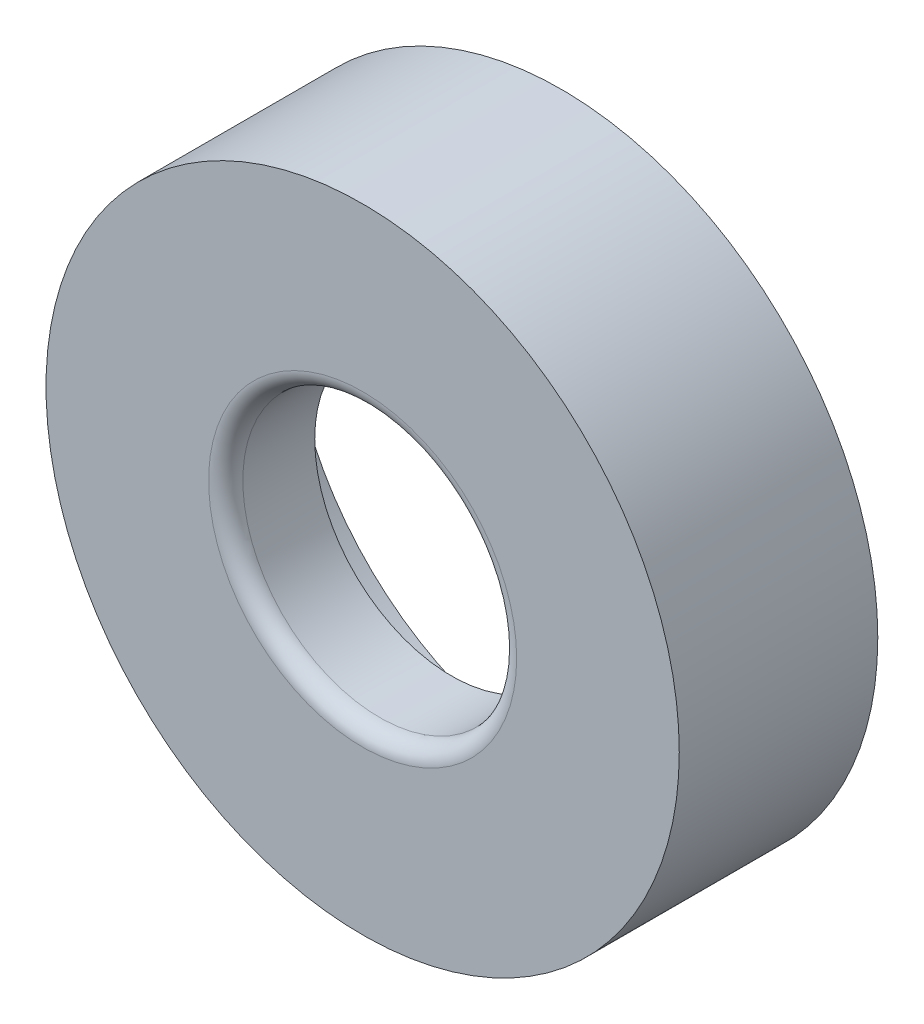
SolidWorks part; units mm, degrees
other "Markup1"
sketch "Sketch4" plane through (94.4065, -10.964, 0) normal (0.175, -0.6068, -0.7753) x (-0.9753, 0.0008, -0.2208)
ref_plane "Front Plane" through (0, 0, 0) normal (0, 0, 1) x (1, 0, 0)
ref_plane "Top Plane" through (0, 0, 0) normal (0, 1, 0) x (1, 0, 0)
ref_plane "Right Plane" through (0, 0, 0) normal (1, 0, 0) x (0, 0, -1)
sketch "Sketch1" plane through (0, 0, 0) normal (0, 0, 1) x (1, 0, 0)
  circle A0 centre (85.2065, -1.764) radius 9.25
  dimension "D1" = 18.5
extrude "Boss-Extrude1" add sketch "Sketch1" along normal blind 5.8
sketch "Sketch2" plane through (0, 0, 5.8) normal (0, 0, 1) x (1, 0, 0)
  circle A0 centre (85.2065, -1.764) radius 4
  dimension "D1" = 8
extrude "Cut-Extrude1" cut sketch "Sketch2" against normal through all
sketch "Sketch3" plane through (0, 0, 0) normal (0, 0, -1) x (-1, 0, 0)
  circle A0 centre (-85.2065, -1.764) radius 7.95
  dimension "D1" = 15.9
extrude "Cut-Extrude2" cut sketch "Sketch3" against normal blind 3.2
fillet "Fillet1" radius 0.5 1 edges at (89.2065, -1.764, 5.8)
